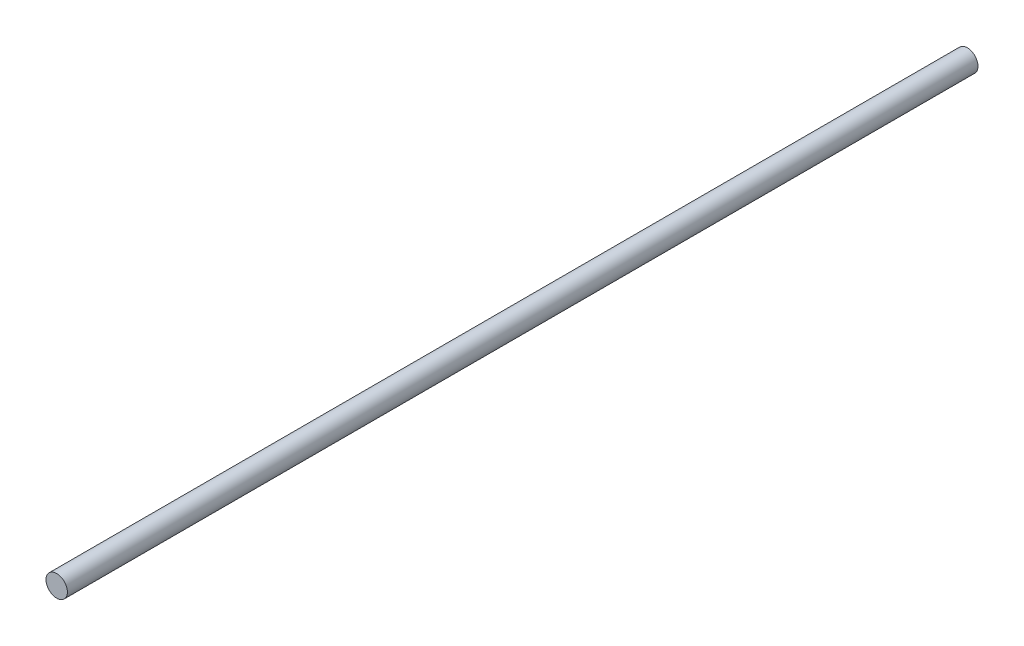
SolidWorks part; units mm, degrees
ref_plane "Alzado" through (0, 0, 0) normal (0, 0, 1) x (1, 0, 0)
ref_plane "Planta" through (0, 0, 0) normal (0, 1, 0) x (1, 0, 0)
ref_plane "Vista lateral" through (0, 0, 0) normal (1, 0, 0) x (0, 0, -1)
sketch "Croquis1" plane through (0, 0, 0) normal (0, 0, 1) x (1, 0, 0)
  circle A0 centre (0, 0) radius 3.175
  dimension "D1" = 6.35
extrude "Saliente-Extruir1" add sketch "Croquis1" along normal mid plane 270
